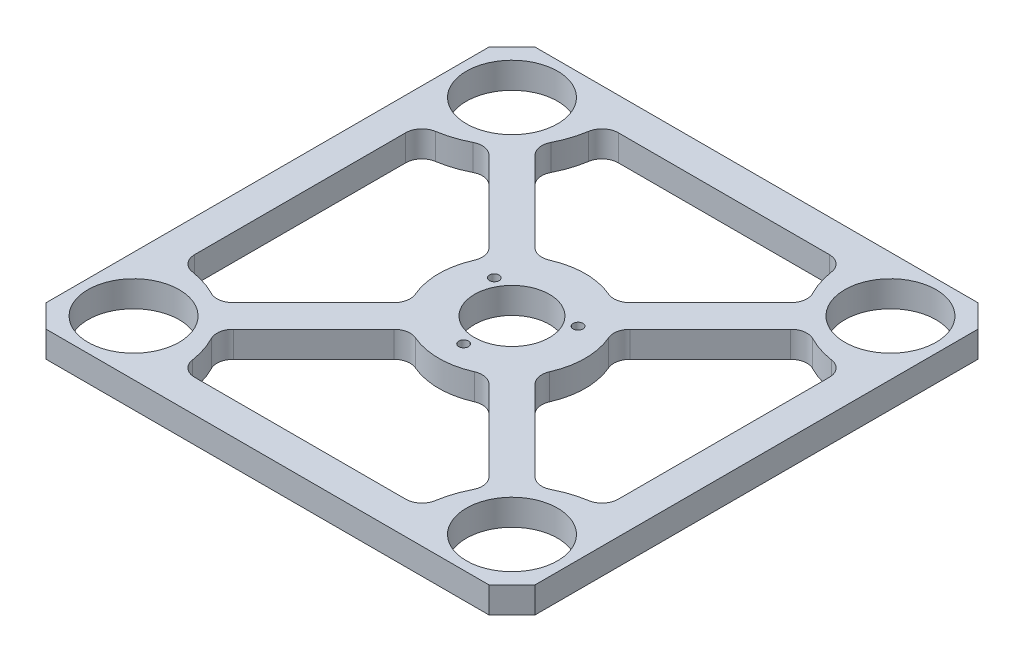
SolidWorks part; units mm, degrees
ref_plane "Front Plane" through (0, 0, 0) normal (0, 0, 1) x (1, 0, 0)
ref_plane "Top Plane" through (0, 0, 0) normal (0, 1, 0) x (1, 0, 0)
ref_plane "Right Plane" through (0, 0, 0) normal (1, 0, 0) x (0, 0, -1)
sketch "Sketch1" plane through (0, 0, 0) normal (0, 1, 0) x (1, 0, 0)
  line L0 (-65, -32.381) -> (-65, 32.381)
  line L1 (-68, -75) -> (68, -75)
  line L2 (-75, -68) -> (-75, 68)
  line L3 (-68, 75) -> (68, 75)
  line L4 (75, -68) -> (75, 68)
  line L5 (-75, -75) -> (75, 75) construction
  line L6 (-75, 75) -> (75, -75) construction
  line L7 (-32.381, 65) -> (32.381, 65)
  line L8 (65, -32.381) -> (65, 32.381)
  line L9 (-32.381, -65) -> (32.381, -65)
  line L10 (0, 0) -> (0, 25.1926) construction
  line L11 (0, 0) -> (19.9526, 0) construction
  line L12 (-39.2271, -46.2982) -> (-14.5787, -21.6498)
  line L13 (-46.2982, -39.2271) -> (-21.6498, -14.5787)
  line L14 (21.6498, -14.5787) -> (46.2982, -39.2271)
  line L15 (21.6498, 14.5787) -> (46.2982, 39.2271)
  line L16 (14.5787, -21.6498) -> (39.2271, -46.2982)
  line L17 (-71.4645, -78.5355) -> (78.5355, 71.4645) construction
  line L18 (14.5787, 21.6498) -> (39.2271, 46.2982)
  line L19 (-78.5355, -71.4645) -> (71.4645, 78.5355) construction
  line L20 (-39.2271, 46.2982) -> (-14.5787, 21.6498)
  line L21 (-65, 65) -> (65, 65) construction
  line L22 (-46.2982, 39.2271) -> (-21.6498, 14.5787)
  line L23 (65, -65) -> (65, 65) construction
  line L24 (-65, -65) -> (65, -65) construction
  line L25 (-65, -65) -> (-65, 65) construction
  line L26 (-75, -75) -> (75, -75) construction
  line L27 (75, -75) -> (75, 75) construction
  line L28 (68, -75) -> (75, -68)
  line L29 (-75, -75) -> (-75, 75) construction
  line L30 (-75, -68) -> (-68, -75)
  line L31 (-75, 75) -> (75, 75) construction
  line L32 (68, 75) -> (75, 68)
  line L33 (-75, 68) -> (-68, 75)
  line L34 (-12.85, 7.419) -> (12.85, 7.419) construction
  line L35 (-12.85, 7.419) -> (0, -14.8379) construction
  line L36 (0, -14.8379) -> (12.85, 7.419) construction
  line L37 (0, 7.419) -> (0, -14.8379) construction
  line L38 (-12.85, 7.419) -> (-11.551, 6.669) construction
  line L39 (12.85, 7.419) -> (-6.425, -3.7095) construction
  line L40 (0, 0) -> (6.425, -3.7095) construction
  arc A1 (-60.7576, 37.3233) -> (-52.1316, 40.1322) centre (-65, 65) ccw
  arc A2 (60.7576, 37.3233) -> (52.1316, 40.1322) centre (65, 65) cw
  arc A3 (60.7576, -37.3233) -> (52.1316, -40.1322) centre (65, -65) ccw
  arc A4 (-60.7576, -37.3233) -> (-52.1316, -40.1322) centre (-65, -65) cw
  arc A5 (-40.1322, 52.1316) -> (-37.3233, 60.7576) centre (-65, 65) ccw
  arc A6 (-40.1322, -52.1316) -> (-37.3233, -60.7576) centre (-65, -65) cw
  arc A7 (40.1322, -52.1316) -> (37.3233, -60.7576) centre (65, -65) ccw
  arc A8 (40.1322, 52.1316) -> (37.3233, 60.7576) centre (65, 65) cw
  arc A9 (20.6061, -9.0353) -> (20.6061, 9.0353) centre (0, 0) ccw
  circle A10 centre (0, 0) radius 11.5
  arc A11 (-9.0353, -20.6061) -> (9.0353, -20.6061) centre (0, 0) ccw
  arc A12 (-20.6061, 9.0353) -> (-20.6061, -9.0353) centre (0, 0) ccw
  arc A13 (9.0353, 20.6061) -> (-9.0353, 20.6061) centre (0, 0) ccw
  circle A14 centre (-58.065, 58.065) radius 14
  circle A15 centre (58.065, 58.065) radius 14
  circle A16 centre (58.065, -58.065) radius 14
  circle A17 centre (-58.065, -58.065) radius 14
  circle A18 centre (-12.85, 7.419) radius 1.5
  circle A19 centre (12.85, 7.419) radius 1.5
  circle A20 centre (0, -14.8379) radius 1.5
  arc A21 (21.6498, -14.5787) -> (20.6061, -9.0353) centre (25.1853, -11.0432) cw
  arc A22 (20.6061, 9.0353) -> (21.6498, 14.5787) centre (25.1853, 11.0432) cw
  arc A23 (14.5787, 21.6498) -> (9.0353, 20.6061) centre (11.0432, 25.1853) cw
  arc A24 (-9.0353, 20.6061) -> (-14.5787, 21.6498) centre (-11.0432, 25.1853) cw
  arc A25 (-21.6498, 14.5787) -> (-20.6061, 9.0353) centre (-25.1853, 11.0432) cw
  arc A26 (-20.6061, -9.0353) -> (-21.6498, -14.5787) centre (-25.1853, -11.0432) cw
  arc A27 (14.5787, -21.6498) -> (9.0353, -20.6061) centre (11.0432, -25.1853) ccw
  arc A28 (-14.5787, -21.6498) -> (-9.0353, -20.6061) centre (-11.0432, -25.1853) cw
  arc A29 (-60.7576, 37.3233) -> (-65, 32.381) centre (-60, 32.381) ccw
  arc A30 (-46.2982, 39.2271) -> (-52.1316, 40.1322) centre (-49.8337, 35.6916) ccw
  arc A31 (-39.2271, 46.2982) -> (-40.1322, 52.1316) centre (-35.6916, 49.8337) cw
  arc A32 (-37.3233, 60.7576) -> (-32.381, 65) centre (-32.381, 60) cw
  arc A33 (40.1322, 52.1316) -> (39.2271, 46.2982) centre (35.6916, 49.8337) cw
  arc A34 (52.1316, 40.1322) -> (46.2982, 39.2271) centre (49.8337, 35.6916) ccw
  arc A35 (60.7576, 37.3233) -> (65, 32.381) centre (60, 32.381) cw
  arc A36 (60.7576, -37.3233) -> (65, -32.381) centre (60, -32.381) ccw
  arc A37 (52.1316, -40.1322) -> (46.2982, -39.2271) centre (49.8337, -35.6916) cw
  arc A38 (40.1322, -52.1316) -> (39.2271, -46.2982) centre (35.6916, -49.8337) ccw
  arc A39 (37.3233, -60.7576) -> (32.381, -65) centre (32.381, -60) cw
  arc A40 (-37.3233, -60.7576) -> (-32.381, -65) centre (-32.381, -60) ccw
  arc A41 (-39.2271, -46.2982) -> (-40.1322, -52.1316) centre (-35.6916, -49.8337) ccw
  arc A42 (-46.2982, -39.2271) -> (-52.1316, -40.1322) centre (-49.8337, -35.6916) cw
  arc A43 (-60.7576, -37.3233) -> (-65, -32.381) centre (-60, -32.381) cw
  arc A44 (37.3233, 60.7576) -> (32.381, 65) centre (32.381, 60) ccw
  point P0 (0, 0)
  point P69 (0, 0)
  point P70 (6.425, -3.7095)
  point P71 (-6.425, -3.7095)
  point P72 (0, 0)
  point P79 (11.9766, 19.0476)
  point P84 (-19.0476, 11.9766)
  point P91 (-11.9766, -19.0476)
  point P98 (-41.9837, 49.0548)
  point P103 (41.9837, 49.0548)
  point P114 (41.9837, -49.0548)
  point P121 (-41.9837, -49.0548)
  dimension "D4" = 28
  dimension "D8" = 23
  dimension "D9" = 45
  dimension "D10" = 5
  dimension "D11" = 28
  dimension "D17" = 3
  dimension "D21" = 5
  dimension "D22" = 5
  dimension "D1" = 150
  dimension "D2" = 150
  dimension "D7" = 5
  dimension "D16" = 19
  dimension "D18" = 25.7
  dimension "D19" = 25.7
  dimension "D20" = 25.7
  dimension "D3" = 10
  dimension "D5" = 5
  dimension "D6" = 5
extrude "Boss-Extrude1" add sketch "Sketch1" along normal mid plane 8
